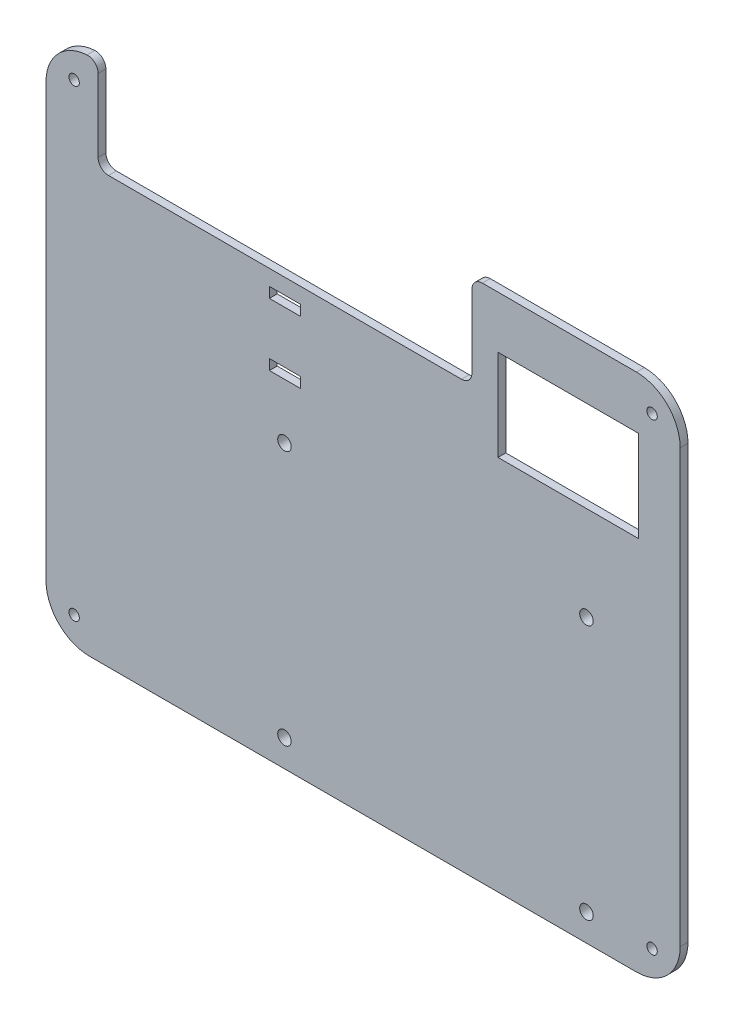
SolidWorks part; units mm, degrees
ref_plane "Ebene vorne" through (0, 0, 0) normal (0, 0, 1) x (1, 0, 0)
ref_plane "Ebene oben" through (0, 0, 0) normal (0, 1, 0) x (1, 0, 0)
ref_plane "Ebene rechts" through (0, 0, 0) normal (1, 0, 0) x (0, 0, -1)
sketch "Skizze1" plane through (0, 0, 0) normal (0, 0, 1) x (1, 0, 0)
  line L0 (0, 8.4) -> (0, 0) construction
  line L1 (8.4, 0) -> (113.4, 0)
  line L2 (0, 8.4) -> (0, 91.4)
  line L3 (8.4, 99.8) -> (113.4, 99.8)
  line L4 (121.8, 8.4) -> (121.8, 91.4)
  line L5 (60.9, 99.8) -> (60.9, 0) construction
  line L6 (0, 49.9) -> (121.8, 49.9) construction
  line L7 (0, 0) -> (8.4, 0) construction
  arc A0 (113.4, 99.8) -> (121.8, 91.4) centre (113.4, 91.4) cw
  arc A1 (121.8, 8.4) -> (113.4, 0) centre (113.4, 8.4) cw
  arc A2 (8.4, 0) -> (0, 8.4) centre (8.4, 8.4) cw
  arc A3 (0, 91.4) -> (8.4, 99.8) centre (8.4, 91.4) cw
  point P6 (121.8, 99.8)
  point P11 (0, 0)
  point P14 (0, 99.8)
  point P160 (60.9, 49.9)
  dimension "D3" = 8.4
  dimension "D1" = 99.8
  dimension "D2" = 121.8
extrude "Aufsatz-Linear austragen1" add sketch "Skizze1" along normal blind 1.5
sketch "Skizze2" plane through (0, 0, 1.5) normal (0, 0, 1) x (1, 0, 0)
  line L0 (0, 91.4) -> (8.4, 91.4) construction
  line L1 (8.4, 91.4) -> (8.4, 99.8) construction
  line L2 (113.4, 0) -> (113.4, 8.4) construction
  line L3 (5.4, 94.4) -> (116.4, 94.4) construction
  line L4 (5.4, 94.4) -> (5.4, 5.4) construction
  line L5 (5.4, 5.4) -> (116.4, 5.4) construction
  line L6 (116.4, 94.4) -> (116.4, 5.4) construction
  line L7 (60.9, 5.4) -> (60.9, 94.4) construction
  line L8 (5.4, 49.9) -> (116.4, 49.9) construction
  line L9 (113.4, 8.4) -> (121.8, 8.4) construction
  line L10 (8.4, 0) -> (113.4, 0) construction
  line L11 (45.8, 54.2) -> (103.8, 54.2) construction
  line L12 (45.8, 54.2) -> (45.8, 5.2) construction
  line L13 (45.8, 5.2) -> (103.8, 5.2) construction
  line L14 (103.8, 54.2) -> (103.8, 5.2) construction
  line L15 (74.8, 5.2) -> (74.8, 54.2) construction
  line L16 (45.8, 29.7) -> (103.8, 29.7) construction
  line L17 (121.8, 8.4) -> (121.8, 91.4) construction
  circle A0 centre (45.8, 54.2) radius 1.3
  circle A1 centre (45.8, 5.2) radius 1.3
  circle A2 centre (103.8, 54.2) radius 1.3
  circle A3 centre (103.8, 5.2) radius 1.3
  circle A4 centre (5.4, 94.4) radius 1
  circle A6 centre (116.4, 94.4) radius 1
  circle A7 centre (116.4, 5.4) radius 1
  circle A8 centre (5.4, 5.4) radius 1
  point P124 (74.8, 29.7)
  point P245 (60.9, 49.9)
  dimension "D1" = 2
  dimension "D2" = 2.6
  dimension "D3" = 3
  dimension "D4" = 3
  dimension "D5" = 3
  dimension "D6" = 3
  dimension "D7" = 58
  dimension "D8" = 49
  dimension "D9" = 5.2
  dimension "D10" = 18
extrude "Schnitt-Linear austragen1" cut sketch "Skizze2" against normal up to next
sketch "Skizze3" plane through (0, 0, 1.5) normal (0, 0, 1) x (1, 0, 0)
  line L1 (86.8, 89.8) -> (113.8, 89.8)
  line L2 (86.8, 89.8) -> (86.8, 72.3)
  line L3 (86.8, 72.3) -> (113.8, 72.3)
  line L4 (113.8, 89.8) -> (113.8, 72.3)
  line L5 (100.3, 72.3) -> (100.3, 89.8) construction
  line L6 (86.8, 81.05) -> (113.8, 81.05) construction
  line L7 (113.4, 99.8) -> (8.4, 99.8) construction
  line L8 (121.8, 8.4) -> (121.8, 91.4) construction
  point P136 (100.3, 81.05)
  dimension "D1" = 17.5
  dimension "D2" = 27
  dimension "D3" = 8
  dimension "D4" = 10
extrude "Schnitt-Linear austragen2" cut sketch "Skizze3" against normal up to next
sketch "Skizze4" plane through (0, 0, 0) normal (0, 0, -1) x (-1, 0, 0)
  circle A0 centre (-103.8, 54.2) radius 2.5
  circle A1 centre (-45.8, 54.2) radius 2.5
  circle A2 centre (-45.8, 5.2) radius 2.5
  circle A3 centre (-103.8, 5.2) radius 2.5
  circle A4 centre (-103.8, 5.2) radius 1.3 construction
  circle A5 centre (-45.8, 5.2) radius 1.3 construction
  circle A6 centre (-45.8, 54.2) radius 1.3 construction
  circle A7 centre (-103.8, 54.2) radius 1.3 construction
  circle A8 centre (-103.8, 5.2) radius 1.3
  circle A9 centre (-45.8, 5.2) radius 1.3
  circle A10 centre (-45.8, 54.2) radius 1.3
  circle A11 centre (-103.8, 54.2) radius 1.3
  dimension "D1" = 5
extrude "Aufsatz-Linear austragen2" add sketch "Skizze4" along normal blind 3
fillet "Verrundung1" radius 2 4 edges at (101.3, 5.2, 0) (43.3, 5.2, 0) (43.3, 54.2, 0) (101.3, 54.2, 0)
sketch "Skizze5" plane through (0, 0, 0) normal (0, 0, -1) x (-1, 0, 0)
  line L0 (-113.4, 99.8) -> (-8.4, 99.8) construction
  line L1 (-81.8, 99.8) -> (-10, 99.8)
  line L2 (-81.8, 99.8) -> (-81.8, 81.8)
  line L3 (-81.8, 81.8) -> (-10, 81.8)
  line L4 (-10, 99.8) -> (-10, 81.8)
  line L5 (-45.9, 81.8) -> (-45.9, 99.8) construction
  line L6 (-81.8, 90.8) -> (-10, 90.8) construction
  line L7 (-86.8, 89.8) -> (-86.8, 72.3) construction
  line L8 (0, 91.4) -> (0, 8.4) construction
  point P180 (-45.9, 90.8)
  dimension "D1" = 18
  dimension "D2" = 10
  dimension "D3" = 5
extrude "Schnitt-Linear austragen3" cut sketch "Skizze5" against normal up to next
fillet "Verrundung2" radius 2 4 edges at (10, 81.8, 0.75) (81.8, 81.8, 0.75) (10, 99.8, 0.75) (81.8, 99.8, 0.75)
sketch "Skizze6" plane through (0, 0, 0) normal (0, 0, -1) x (-1, 0, 0)
  line L0 (-45.9, 81.8) -> (-45.9, 0) construction
  line L1 (-48.9, 78.8) -> (-42.9, 78.8)
  line L2 (-48.9, 78.8) -> (-48.9, 76.8)
  line L3 (-48.9, 76.8) -> (-42.9, 76.8)
  line L4 (-42.9, 78.8) -> (-42.9, 76.8)
  line L5 (-45.9, 76.8) -> (-45.9, 78.8) construction
  line L6 (-48.9, 77.8) -> (-42.9, 77.8) construction
  line L7 (-48.9, 66.8) -> (-42.9, 66.8)
  line L8 (-48.9, 66.8) -> (-48.9, 64.8)
  line L9 (-48.9, 64.8) -> (-42.9, 64.8)
  line L10 (-42.9, 66.8) -> (-42.9, 64.8)
  line L11 (-45.9, 64.8) -> (-45.9, 66.8) construction
  line L12 (-48.9, 65.8) -> (-42.9, 65.8) construction
  line L13 (-79.8, 81.8) -> (-12, 81.8) construction
  line L14 (-8.4, 0) -> (-113.4, 0) construction
  point P76 (-45.9, 77.8)
  point P105 (-45.9, 65.8)
  dimension "D1" = 10
  dimension "D2" = 6
  dimension "D3" = 2
  dimension "D4" = 3
extrude "Schnitt-Linear austragen4" cut sketch "Skizze6" against normal up to next
